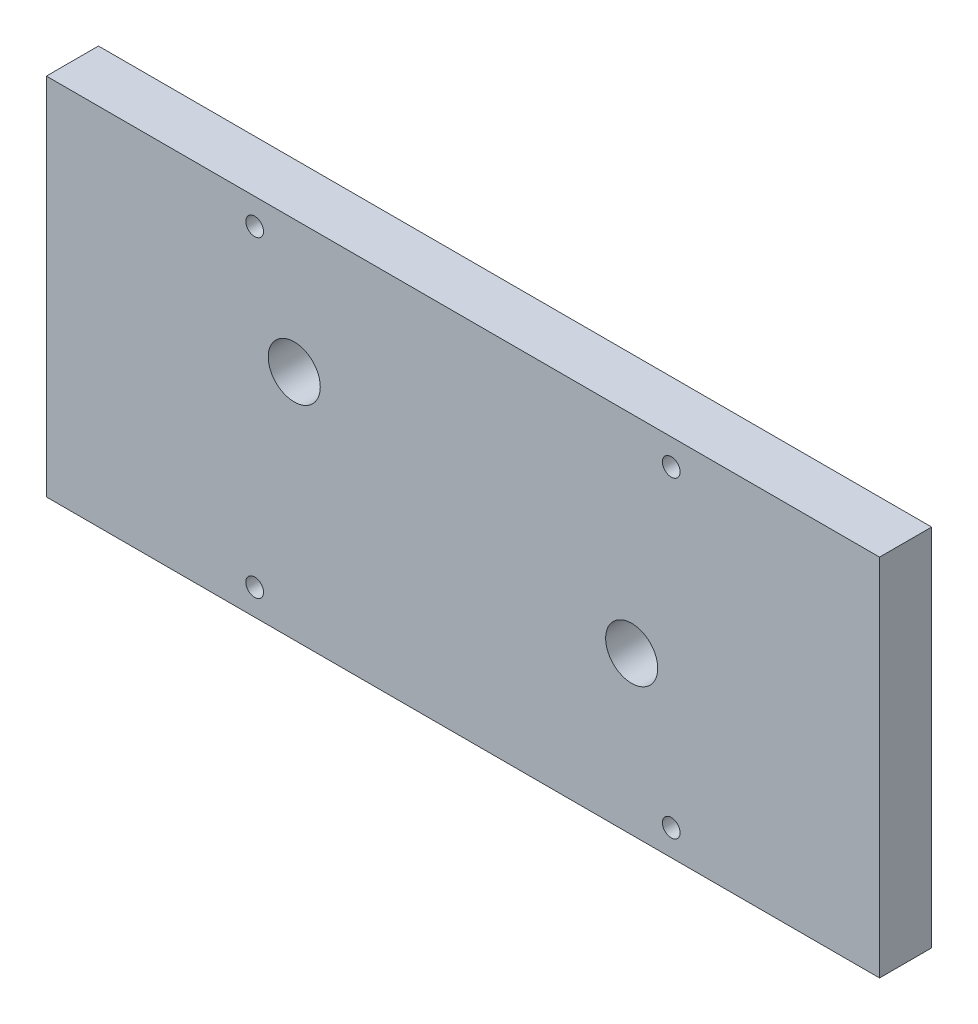
SolidWorks part; units mm, degrees
material "Náilon 6/10"
ref_plane "Plano frontal" through (0, 0, 0) normal (0, 0, 1) x (1, 0, 0)
ref_plane "Plano superior" through (0, 0, 0) normal (0, 1, 0) x (1, 0, 0)
ref_plane "Plano direito" through (0, 0, 0) normal (1, 0, 0) x (0, 0, -1)
sketch "Esboço1" plane through (0, 0, 92.2731) normal (0, 0, -1) x (-1, 0, 0)
  line L0 (-21.9475, 570.1087) -> (155.5793, 570.1087) construction
  line L1 (146.8193, 520.1087) -> (-13.1807, 520.1087)
  line L2 (146.8193, 520.1087) -> (146.8193, 450.1087)
  line L3 (146.8193, 450.1087) -> (-13.1807, 450.1087)
  line L4 (-13.1807, 520.1087) -> (-13.1807, 450.1087)
  line L5 (155.5793, 570.1087) -> (155.5793, 356.5853) construction
  dimension "D1" = 70
  dimension "D2" = 160
  dimension "D3" = 50
  dimension "D4" = 8.76
extrude "Ressalto-extrusão1" add sketch "Esboço1" along normal blind 10
hole_wizard "Furo com folga de M33" positions "Esboço5" profile "Esboço4" hole size "M3" standard "Métrico Ansi" end condition up to next
sketch "Esboço5" plane through (0, 0, 92.2731) normal (0, 0, 1) x (1, 0, 0)
  point P0 (-106.8193, 515.1087)
  point P1 (-26.8193, 515.1087)
  point P4 (-26.8193, 455.1087)
  point P7 (-106.8193, 455.1087)
sketch "Esboço4" plane through (-106.8193, 515.1087, 92.2731) normal (1, 0, 0) x (0, -1, 0)
  line L0 (0, 0) -> (0, 10)
  line L1 (0, 10) -> (1.7, 10)
  line L2 (1.7, 10) -> (1.7, 0)
  line L5 (1.7, 0) -> (0, 0)
  line L11 (0, -6.35) -> (0, 107.95) construction
  dimension "Thru Hole Dia." = 3.4
  dimension "Thru Hole Depth" = 10
sketch "Esboço6" plane through (0, 0, 93.7731) normal (0, 0, 1) x (1, 0, 0)
  line L0 (-146.8193, 520.1087) -> (13.1807, 520.1087) construction
  line L1 (-146.8193, 450.1087) -> (-146.8193, 520.1087) construction
  line L2 (13.1807, 520.1087) -> (13.1807, 450.1087) construction
  circle A0 centre (-34.4193, 480.3087) radius 5
  circle A1 centre (-99.2193, 494.7087) radius 5
  dimension "D1" = 10
  dimension "D2" = 10
  dimension "D3" = 25.4
  dimension "D4" = 47.6
  dimension "D5" = 39.8
  dimension "D6" = 47.6
extrude "Corte-extrusão1" cut sketch "Esboço6" against normal blind 10
hole_wizard "Furo com folga de M61" positions "Esboço8" profile "Esboço7" hole size "M6" standard "Métrico Ansi" end condition up to next
sketch "Esboço8" plane through (0, 0, 83.7731) normal (0, 0, 1) x (1, 0, 0)
  point P0 (-99.2193, 494.7087)
  point P1 (-34.4193, 480.3087)
sketch "Esboço7" plane through (-99.2193, 494.7087, 83.7731) normal (1, 0, 0) x (0, -1, 0)
  line L0 (0, 0) -> (0, 1.5)
  line L1 (0, 1.5) -> (3.3, 1.5)
  line L2 (3.3, 1.5) -> (3.3, 0)
  line L5 (3.3, 0) -> (0, 0)
  line L11 (0, -6.35) -> (0, 107.95) construction
  dimension "Thru Hole Dia." = 6.6
  dimension "Thru Hole Depth" = 1.5
